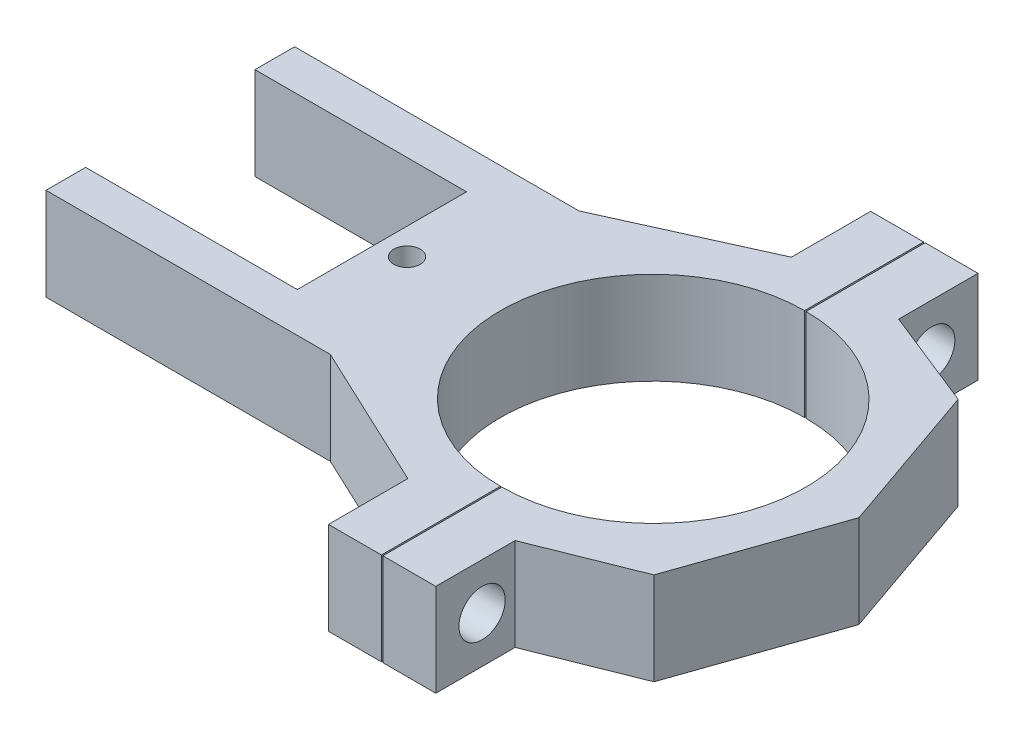
SolidWorks part; units mm, degrees
ref_plane "Спереди" through (0, 0, 0) normal (0, 0, 1) x (1, 0, 0)
ref_plane "Сверху" through (0, 0, 0) normal (0, 1, 0) x (1, 0, 0)
ref_plane "Справа" through (0, 0, 0) normal (1, 0, 0) x (0, 0, -1)
sketch "Эскиз1" plane through (0, 0, 0) normal (0, 1, 0) x (1, 0, 0)
  line L0 (-13.2478, 6.0171) -> (-13.2478, 3.0171)
  line L1 (-13.2478, 3.0171) -> (2.7522, 3.0171)
  line L2 (2.7522, 3.0171) -> (2.7522, -9.7829)
  line L3 (2.7522, -9.7829) -> (-13.2478, -9.7829)
  line L4 (-13.2478, -9.7829) -> (-13.2478, -12.7829)
  line L5 (-13.2478, -12.7829) -> (8.2522, -12.7829)
  line L6 (-13.2478, 6.0171) -> (8.2522, 6.0171)
  line L7 (23.3112, 8.0171) -> (23.3112, 17.0171)
  line L8 (23.3112, -14.9829) -> (23.3112, -23.9829)
  line L9 (23.3112, 17.0171) -> (19.3112, 17.0171)
  line L10 (23.3112, -23.9829) -> (19.3112, -23.9829)
  line L11 (19.3112, 17.0171) -> (19.3112, 11.0171)
  line L12 (19.3112, -23.9829) -> (19.3112, -17.9829)
  line L13 (19.3112, 11.0171) -> (8.2522, 6.0171)
  line L14 (19.3112, -17.9829) -> (8.2522, -12.7829)
  circle A0 centre (23.3112, -3.4829) radius 11.5 construction
  arc A3 (23.3112, 8.0171) -> (23.3112, -14.9829) centre (23.3112, -3.4829) ccw
  dimension "D4" = 20.559
  dimension "D9" = 11.5
  dimension "D1" = 3
  dimension "D3" = 12.8
  dimension "D5" = 16
  dimension "D6" = 9
  dimension "D7" = 4
  dimension "D8" = 6
sketch "Эскиз2" plane through (0, 0, 0) normal (0, 1, 0) x (1, 0, 0)
  line L0 (23.425, -14.9823) -> (23.425, -23.9823)
  line L1 (23.425, -23.9823) -> (27.425, -23.9823)
  line L2 (27.425, -23.9823) -> (27.425, -17.9823)
  line L3 (23.425, 8.0165) -> (23.425, 17.0165)
  line L4 (23.425, 17.0165) -> (27.425, 17.0165)
  line L5 (27.425, 17.0165) -> (27.425, 11.0165)
  line L6 (27.425, 11.0165) -> (34.9244, 8.0165)
  line L7 (34.9244, 8.0165) -> (38.925, -3.4829)
  line L8 (38.925, -3.4829) -> (34.9244, -14.9823)
  line L9 (34.9244, -14.9823) -> (27.425, -17.9823)
  circle A1 centre (23.3112, -3.4829) radius 11.5 construction
  arc A2 (23.425, -14.9823) -> (23.425, 8.0165) centre (23.425, -3.4829) ccw
  point P8 (38.925, -3.4829)
  point P12 (38.925, 11.0165)
  point P13 (38.925, -17.9823)
  point P14 (34.9244, 8.0165)
  point P15 (34.9244, -14.9823)
  dimension "D4" = 11.4994
  dimension "D5" = 15.5
  dimension "D1" = 9
  dimension "D2" = 4
  dimension "D3" = 6
extrude "Бобышка-Вытянуть1" add sketch "Эскиз1" along normal blind 7
extrude "Бобышка-Вытянуть2" add sketch "Эскиз2" along normal blind 7 separate body
sketch "Эскиз4" plane through (19.3112, 0, 0) normal (-1, 0, 0) x (0, 0, 1)
  line L0 (-17.0171, 7) -> (-17.0171, 0) construction
  circle A0 centre (-13.5171, 3.5) radius 1.75
  point P2 (-17.0171, 3.5)
  dimension "D1" = 3.5
  dimension "D2" = 3.5
sketch "Эскиз6" plane through (19.3112, 0, 0) normal (-1, 0, 0) x (0, 0, 1)
  line L0 (23.9829, 7) -> (23.9829, 0) construction
  circle A0 centre (20.4829, 3.5) radius 1.75
  point P2 (23.9829, 3.5)
  dimension "D1" = 3.5
  dimension "D2" = 3.5
extrude "Вырез-Вытянуть1" cut sketch "Эскиз6" against normal through all
extrude "Вырез-Вытянуть2" cut sketch "Эскиз4" against normal through all
sketch "Эскиз7" plane through (0, 7, 0) normal (0, 1, 0) x (1, 0, 0)
  line L0 (2.7522, 3.0171) -> (2.7522, -9.7829) construction
  circle A0 centre (4.7497, -3.4828) radius 1
  point P2 (2.7522, -3.3829)
  dimension "D2" = 2
  dimension "D1" = 2
extrude "Вырез-Вытянуть3" cut sketch "Эскиз7" against normal through all
